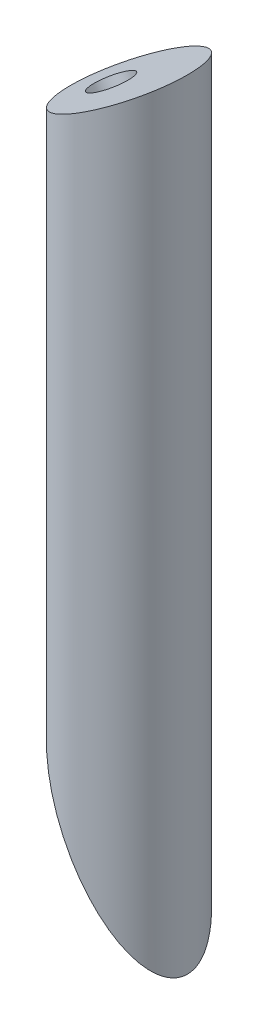
SolidWorks part; units mm, degrees
ref_plane "Front Plane" through (0, 0, 0) normal (0, 0, 1) x (1, 0, 0)
ref_plane "Top Plane" through (0, 0, 0) normal (0, 1, 0) x (1, 0, 0)
ref_plane "Right Plane" through (0, 0, 0) normal (1, 0, 0) x (0, 0, -1)
sketch "Sketch1" plane through (0, 0, 0) normal (0, 1, 0) x (1, 0, 0)
  circle A0 centre (0, 0) radius 7.5
  dimension "D1" = 15
extrude "Boss-Extrude1" add sketch "Sketch1" along normal blind 100
sketch "Sketch2" plane through (0, 0, 0) normal (0, 0, 1) x (1, 0, 0)
  line L0 (7.5, 0) -> (-11.156, 32.3132)
  line L4 (7.5, 100) -> (-22.6082, 82.617)
  line L5 (-22.6082, 82.617) -> (-22.6082, 113.4043)
  line L6 (-22.6082, 113.4043) -> (7.5, 113.4043)
  line L7 (7.5, 113.4043) -> (7.5, 100)
  line L8 (7.5, 100) -> (-7.5, 100) construction
  line L9 (-7.5, 0) -> (7.5, 0) construction
  line L10 (-11.156, 32.3132) -> (-11.156, -9.9862)
  line L11 (-11.156, -9.9862) -> (7.5, -9.9862)
  line L12 (7.5, -9.9862) -> (7.5, 0)
  dimension "D1" = 30
  dimension "D2" = 60
extrude "Cut-Extrude1" cut sketch "Sketch2" against normal mid plane 100
sketch "Sketch3" plane through (-41.4263, 71.7524, 0) normal (-0.5, 0.866, 0) x (0.866, 0.5, 0)
  circle A0 centre (45.1747, 0) radius 2.5
  ellipse E0 centre (47.8349, 0) end of major axis (39.1747, 0) minor radius 7.5 construction
  point P8 (39.1747, 0)
  dimension "D1" = 6
extrude "Cut-Extrude2" cut sketch "Sketch3" against normal blind 10
sketch "Sketch4" plane through (5.625, 3.2476, 0) normal (-0.866, -0.5, 0) x (0, 0, 1)
  circle A0 centre (0, 18.25) radius 2.5
  ellipse E0 centre (0, 11.25) end of major axis (0, -3.75) minor radius 7.5 construction
  point P2 (0, 26.25)
  dimension "D1" = 8
extrude "Cut-Extrude3" cut sketch "Sketch4" against normal blind 7
